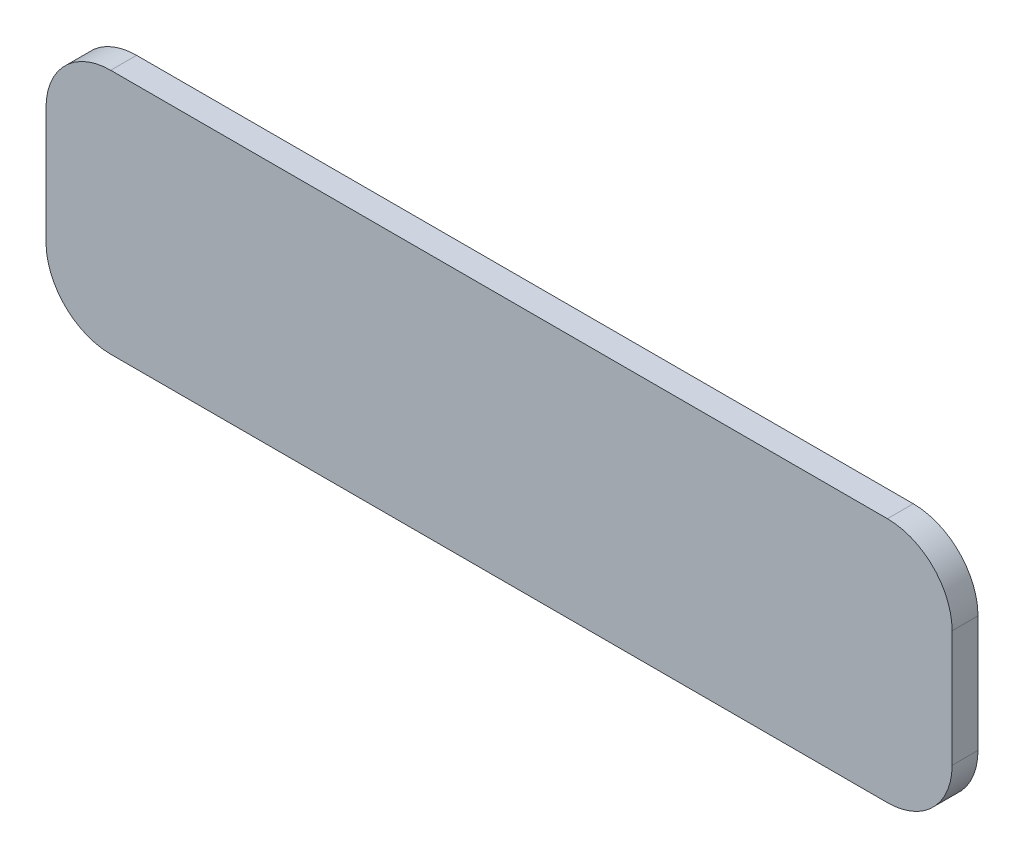
SolidWorks part; units mm, degrees
ref_plane "前视基准面" through (0, 0, 0) normal (0, 0, 1) x (1, 0, 0)
ref_plane "上视基准面" through (0, 0, 0) normal (0, 1, 0) x (1, 0, 0)
ref_plane "右视基准面" through (0, 0, 0) normal (1, 0, 0) x (0, 0, -1)
sketch "草图1" plane through (0, 0, 0) normal (0, 0, 1) x (1, 0, 0)
  line L1 (5, 0) -> (65, 0)
  line L2 (0, 5) -> (0, 14)
  line L3 (5, 19) -> (65, 19)
  line L4 (70, 5) -> (70, 14)
  arc A0 (5, 0) -> (0, 5) centre (5, 5) cw
  arc A1 (65, 0) -> (70, 5) centre (65, 5) ccw
  arc A2 (65, 19) -> (70, 14) centre (65, 14) cw
  arc A3 (0, 14) -> (5, 19) centre (5, 14) cw
  point P7 (0, 0)
  point P10 (70, 0)
  point P15 (0, 19)
  dimension "D3" = 5
  dimension "D1" = 70
  dimension "D2" = 19
extrude "凸台-拉伸1" add sketch "草图1" along normal blind 2
ref_plane "基准面1" through (35, 0, 0) normal (-1, 0, 0) x (0, 0, 1)
